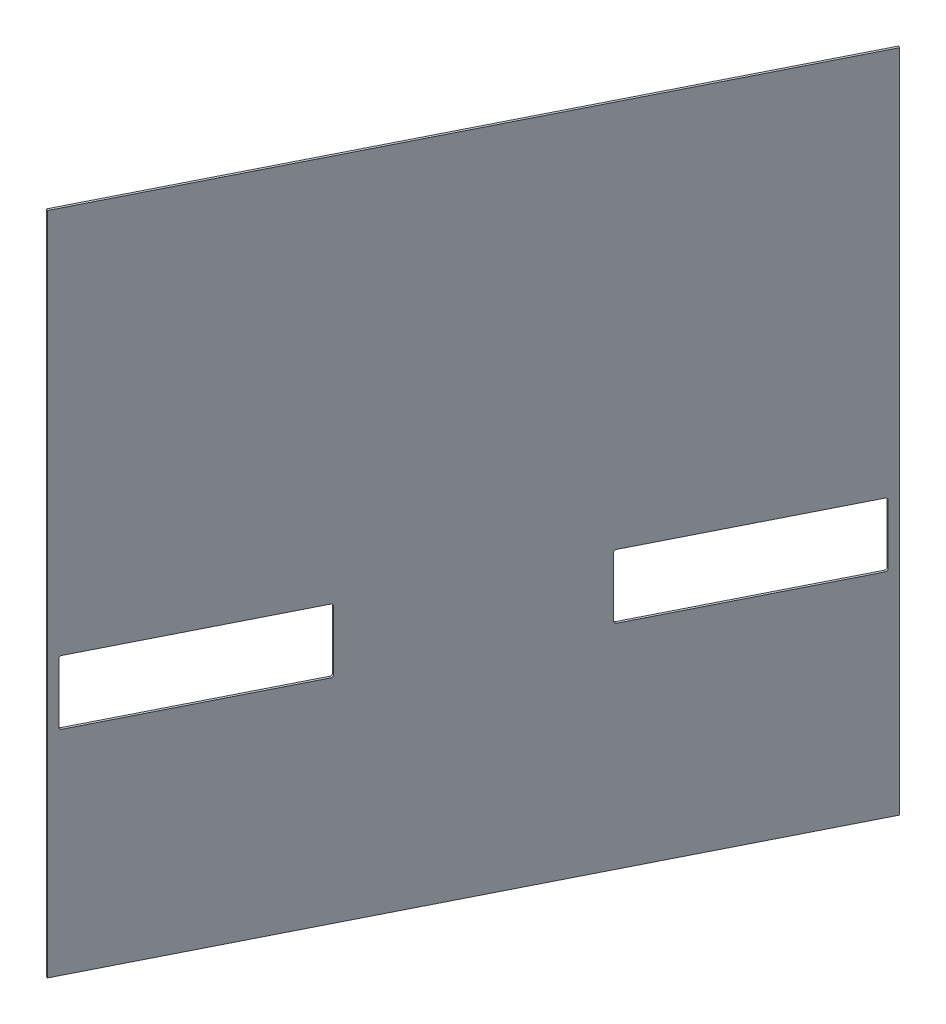
SolidWorks part; units mm, degrees
ref_plane "Front Plane" through (0, 0, 0) normal (0, 0, 1) x (1, 0, 0)
ref_plane "Top Plane" through (0, 0, 0) normal (0, 1, 0) x (1, 0, 0)
ref_plane "Right Plane" through (0, 0, 0) normal (1, 0, 0) x (0, 0, -1)
sketch "Sketch1" plane through (-4014.6274, 0, -2017.5074) normal (0.8935, 0, 0.449) x (0.449, 0, -0.8935)
  line L4 (5982.8035, 6.35) -> (5982.8035, 1987.55)
  line L5 (5982.8035, 1987.55) -> (5036.6535, 1987.55)
  line L6 (5036.6535, 1987.55) -> (5036.6535, 6.35)
  line L7 (5036.6535, 6.35) -> (5982.8035, 6.35)
  line L9 (5982.8035, 1987.55) -> (5036.6535, 1987.55)
  line L10 (5036.6535, 1987.55) -> (5036.6535, 6.35)
  line L11 (5036.6535, 6.35) -> (5982.8035, 6.35)
  line L12 (6928.9535, 1987.55) -> (5982.8035, 1987.55)
  line L13 (6928.9535, 1987.55) -> (5982.8035, 1987.55)
  line L14 (5982.8035, 1987.55) -> (5982.8035, 6.35)
  line L16 (5982.8035, 6.35) -> (6928.9535, 6.35)
  line L17 (5982.8035, 6.35) -> (6928.9535, 6.35)
  line L18 (6928.9535, 6.35) -> (6928.9535, 1987.55)
  line L19 (6928.9535, 6.35) -> (6928.9535, 1987.55)
  line L20 (6293.9535, 825.5) -> (6293.9535, 647.7)
  line L21 (6897.2035, 831.85) -> (6300.3035, 831.85)
  line L22 (6903.5535, 647.7) -> (6903.5535, 825.5)
  line L23 (6300.3035, 641.35) -> (6897.2035, 641.35)
  line L24 (6293.9535, 825.5) -> (6293.9535, 647.7)
  line L25 (6897.2035, 831.85) -> (6300.3035, 831.85)
  line L26 (6903.5535, 647.7) -> (6903.5535, 825.5)
  line L27 (6300.3035, 641.35) -> (6897.2035, 641.35)
  line L28 (5068.4035, 641.35) -> (5665.3035, 641.35)
  line L29 (5062.0535, 825.5) -> (5062.0535, 647.7)
  line L30 (5665.3035, 831.85) -> (5068.4035, 831.85)
  line L31 (5671.6535, 647.7) -> (5671.6535, 825.5)
  line L32 (5068.4035, 641.35) -> (5665.3035, 641.35)
  line L33 (5062.0535, 825.5) -> (5062.0535, 647.7)
  line L34 (5665.3035, 831.85) -> (5068.4035, 831.85)
  line L35 (5671.6535, 647.7) -> (5671.6535, 825.5)
  arc A12 (6293.9535, 647.7) -> (6300.3035, 641.35) centre (6300.3035, 647.7) ccw
  arc A13 (6300.3035, 831.85) -> (6293.9535, 825.5) centre (6300.3035, 825.5) ccw
  arc A14 (6903.5535, 825.5) -> (6897.2035, 831.85) centre (6897.2035, 825.5) ccw
  arc A15 (6897.2035, 641.35) -> (6903.5535, 647.7) centre (6897.2035, 647.7) ccw
  arc A16 (6293.9535, 647.7) -> (6300.3035, 641.35) centre (6300.3035, 647.7) ccw
  arc A17 (6300.3035, 831.85) -> (6293.9535, 825.5) centre (6300.3035, 825.5) ccw
  arc A18 (6903.5535, 825.5) -> (6897.2035, 831.85) centre (6897.2035, 825.5) ccw
  arc A19 (6897.2035, 641.35) -> (6903.5535, 647.7) centre (6897.2035, 647.7) ccw
  arc A20 (5062.0535, 647.7) -> (5068.4035, 641.35) centre (5068.4035, 647.7) ccw
  arc A21 (5068.4035, 831.85) -> (5062.0535, 825.5) centre (5068.4035, 825.5) ccw
  arc A22 (5671.6535, 825.5) -> (5665.3035, 831.85) centre (5665.3035, 825.5) ccw
  arc A23 (5665.3035, 641.35) -> (5671.6535, 647.7) centre (5665.3035, 647.7) ccw
  arc A24 (5062.0535, 647.7) -> (5068.4035, 641.35) centre (5068.4035, 647.7) ccw
  arc A25 (5068.4035, 831.85) -> (5062.0535, 825.5) centre (5068.4035, 825.5) ccw
  arc A26 (5671.6535, 825.5) -> (5665.3035, 831.85) centre (5665.3035, 825.5) ccw
  arc A27 (5665.3035, 641.35) -> (5671.6535, 647.7) centre (5665.3035, 647.7) ccw
  dimension "D1" = 0
  dimension "D2" = 0
  dimension "D3" = 0
  dimension "D4" = 0
extrude "Boss-Extrude1" add sketch "Sketch1" against normal up to surface (6.35 mm away)
